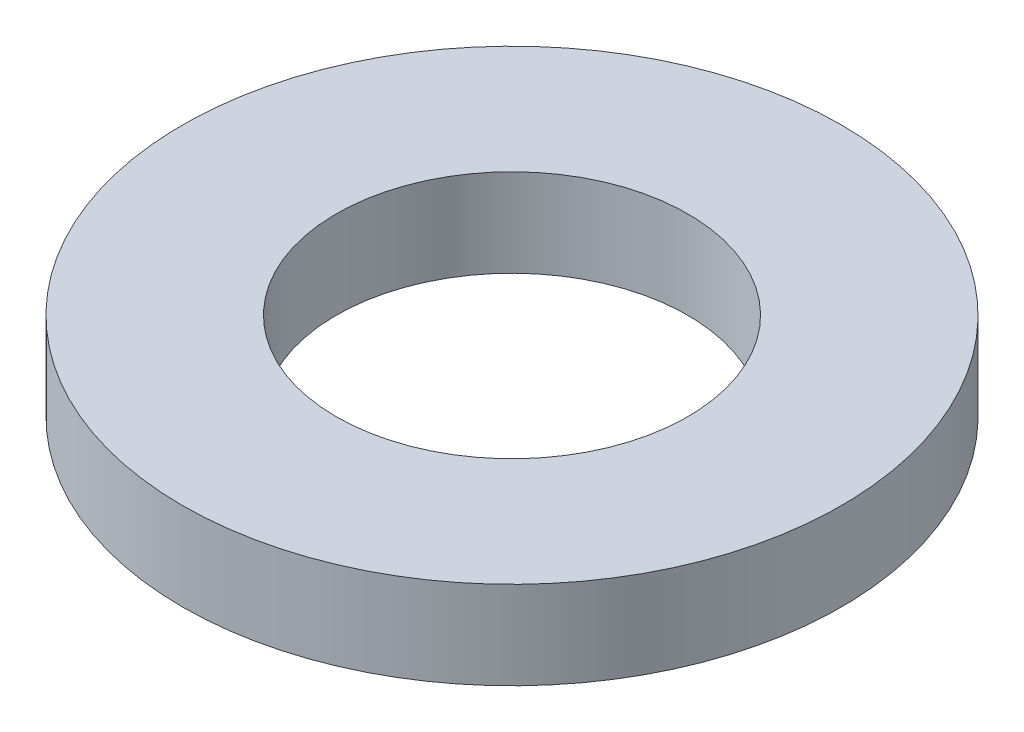
SolidWorks part; units mm, degrees
ref_plane "Front Plane" through (0, 0, 0) normal (0, 0, 1) x (1, 0, 0)
ref_plane "Top Plane" through (0, 0, 0) normal (0, 1, 0) x (1, 0, 0)
ref_plane "Right Plane" through (0, 0, 0) normal (1, 0, 0) x (0, 0, -1)
sketch "Sketch1" plane through (0, 0, 0) normal (0, 1, 0) x (1, 0, 0)
  circle A0 centre (0, 0) radius 11.9062
  circle A1 centre (0, 0) radius 6.35
  dimension "D1" = 12.7
  dimension "D2" = 23.8125
extrude "Boss-Extrude1" add sketch "Sketch1" along normal blind 3.175
